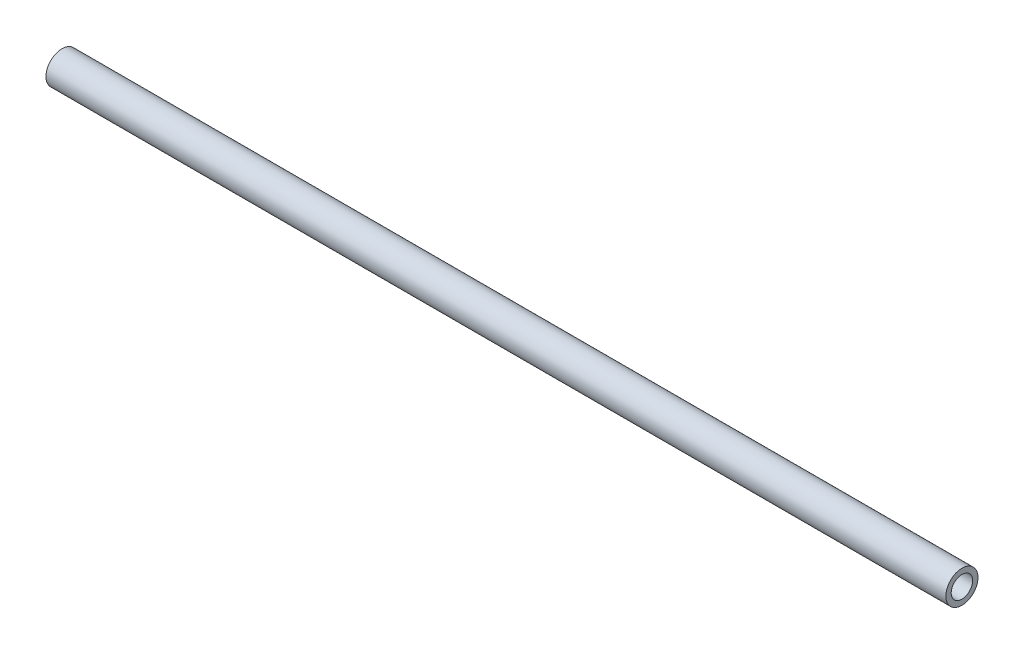
SolidWorks part; units mm, degrees
ref_plane "Front" through (0, 0, 0) normal (0, 0, 1) x (1, 0, 0)
ref_plane "Top" through (0, 0, 0) normal (0, 1, 0) x (1, 0, 0)
ref_plane "Right" through (0, 0, 0) normal (1, 0, 0) x (0, 0, -1)
sketch "Sketch1" plane through (0, 0, 0) normal (1, 0, 0) x (0, 0, -1)
  line L0 (6.35, 0) -> (9.525, 0) construction
  line L1 (6.35, 0) -> (9.525, 0) construction
  line L2 (7.9375, 0) -> (7.9375, 1.0672) construction
  circle A0 centre (0, 0) radius 9.525
  circle A1 centre (0, 0) radius 6.35
  point P4 (9.525, 0)
  point P5 (6.35, 0)
  dimension "OD" = 19.05
  dimension "ID" = 12.7
  dimension "Wall Thickness" = 3.175
sketch "Sketch2" plane through (0, 0, 0) normal (0, 0, 1) x (1, 0, 0)
  line L0 (-266.7, 0) -> (266.7, 0) construction
  point P2 (-242.8875, 0)
  point P3 (242.8875, 0)
  dimension "D1" = 23.8125
  dimension "D2" = 23.8125
sketch "Sketch3" plane through (0, 0, 0) normal (1, 0, 0) x (0, 0, -1)
  circle A0 centre (0, 0) radius 6.35 construction
  circle A1 centre (0, 0) radius 9.525 construction
  circle A2 centre (0, 0) radius 6.35
  circle A3 centre (0, 0) radius 9.525
extrude "Boss-Extrude1" add sketch "Sketch3" along normal mid plane 533.4
equation "\"D1@Boss-Extrude1\"=\"Length@Sketch2\""
equation "\"D1@Sketch2\"=\"OD@Sketch1\"*1.25"
equation "\"D2@Sketch2\"=\"D1@Sketch2\""
